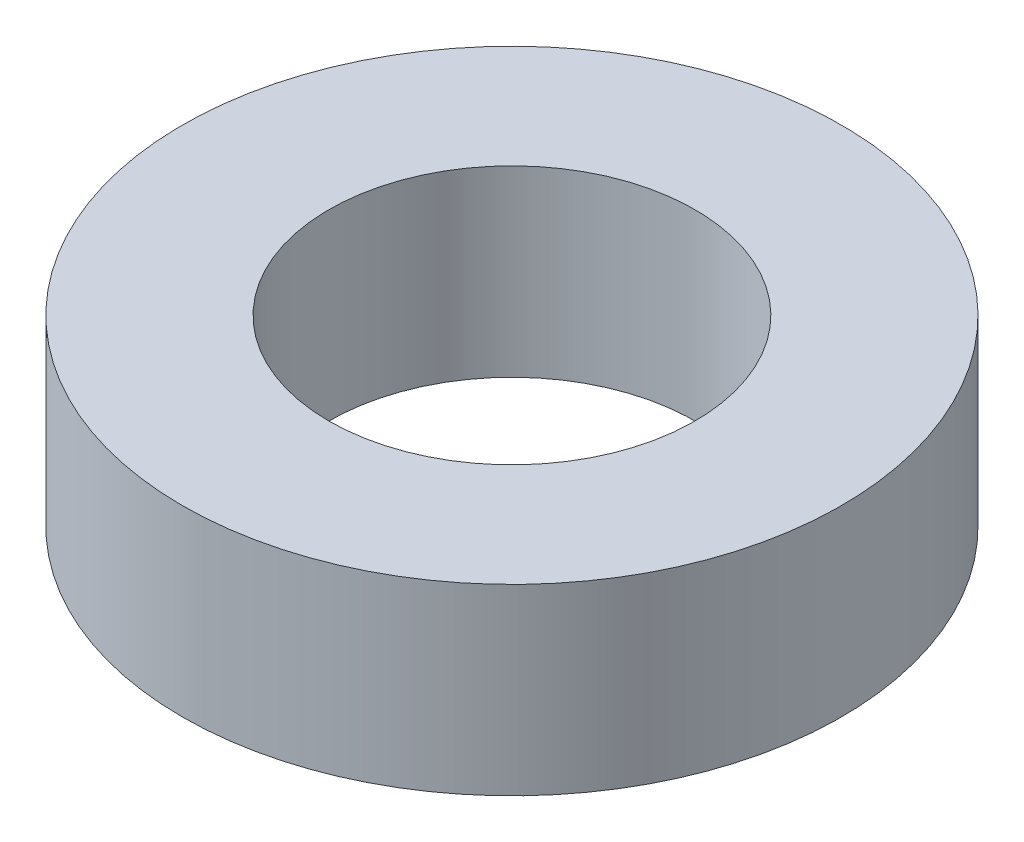
SolidWorks part; units mm, degrees
ref_plane "Front Plane" through (0, 0, 0) normal (0, 0, 1) x (1, 0, 0)
ref_plane "Top Plane" through (0, 0, 0) normal (0, 1, 0) x (1, 0, 0)
ref_plane "Right Plane" through (0, 0, 0) normal (1, 0, 0) x (0, 0, -1)
sketch "Sketch1" plane through (0, 0, 0) normal (0, 1, 0) x (1, 0, 0)
  circle A0 centre (0, 0) radius 2.5
  circle A1 centre (0, 0) radius 4.5
  dimension "D1" = 5
  dimension "D2" = 9
extrude "Boss-Extrude1" add sketch "Sketch1" along normal blind 2.5
